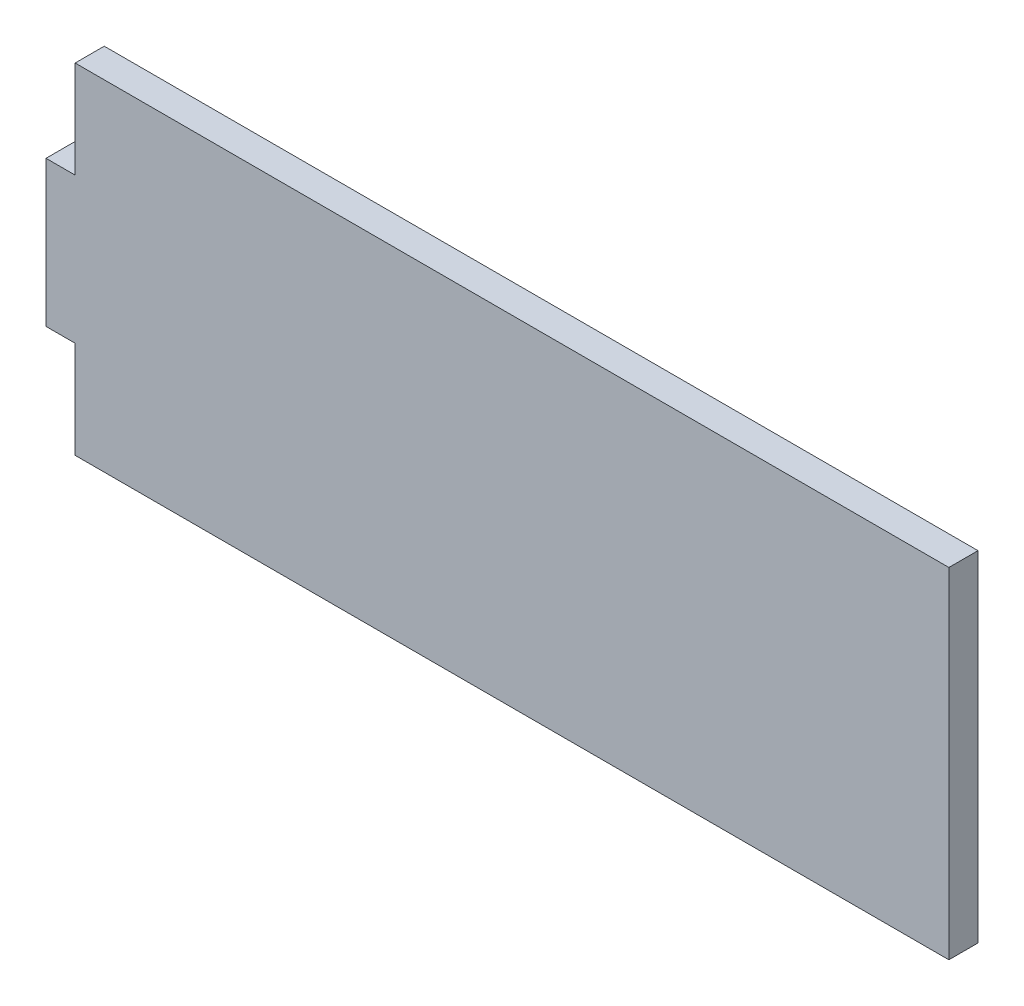
SolidWorks part; units mm, degrees
ref_plane "Front Plane" through (0, 0, 0) normal (0, 0, 1) x (1, 0, 0)
ref_plane "Top Plane" through (0, 0, 0) normal (0, 1, 0) x (1, 0, 0)
ref_plane "Right Plane" through (0, 0, 0) normal (1, 0, 0) x (0, 0, -1)
sketch "Sketch1" plane through (0, 0, 0) normal (0, 0, 1) x (1, 0, 0)
  line L1 (-45, -17.5) -> (45, -17.5)
  line L2 (-45, -17.5) -> (-45, 17.5)
  line L3 (-45, 17.5) -> (45, 17.5)
  line L4 (45, -17.5) -> (45, 17.5)
  line L5 (-45, -17.5) -> (45, 17.5) construction
  line L6 (-45, 17.5) -> (45, -17.5) construction
  line L7 (-45, 7.5) -> (-48, 7.5)
  line L8 (-45, 7.5) -> (-45, -7.5)
  line L9 (-45, -7.5) -> (-48, -7.5)
  line L10 (-48, 7.5) -> (-48, -7.5)
  point P0 (0, 0)
  point P10 (-48, 0)
  point P11 (-46.5, -7.5)
  dimension "D1" = 90
  dimension "D2" = 10
  dimension "D3" = 15
  dimension "D4" = 3
extrude "Boss-Extrude1" add sketch "Sketch1" along normal mid plane 3 contours L1 L4 L3 L2 | L7 L10 L9 L2
